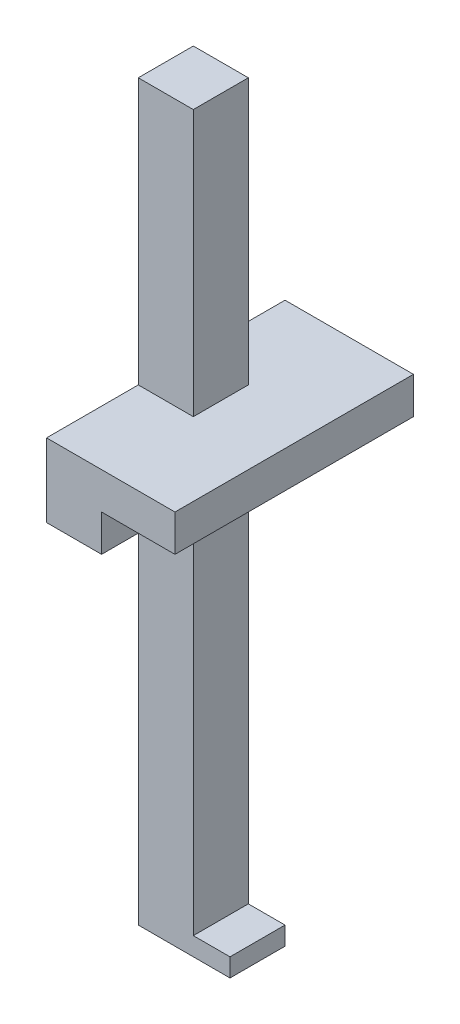
SolidWorks part; units mm, degrees
ref_plane "Front Plane" through (0, 0, 0) normal (0, 0, 1) x (1, 0, 0)
ref_plane "Top Plane" through (0, 0, 0) normal (0, 1, 0) x (1, 0, 0)
ref_plane "Right Plane" through (0, 0, 0) normal (1, 0, 0) x (0, 0, -1)
sketch "Sketch1" plane through (0, 0, 0) normal (0, 0, 1) x (1, 0, 0)
  line L0 (0, 0) -> (0, 40)
  line L1 (0, 40) -> (3, 40)
  line L2 (3, 40) -> (3, 1)
  line L3 (3, 1) -> (5, 1)
  line L4 (5, 1) -> (5, 0)
  line L5 (5, 0) -> (0, 0)
  dimension "D1" = 1
  dimension "D2" = 5
  dimension "D3" = 40
  dimension "D4" = 3
extrude "Boss-Extrude1" add sketch "Sketch1" along normal blind 3
sketch "Sketch2" plane through (0, 0, 3) normal (0, 0, 1) x (1, 0, 0)
  line L0 (0, 40) -> (0, 0) construction
  line L1 (0, 25.5) -> (3, 25.5)
  line L2 (0, 25.5) -> (0, 21.5)
  line L3 (0, 21.5) -> (3, 21.5)
  line L4 (3, 25.5) -> (3, 21.5)
  line L5 (3, 1) -> (3, 40) construction
  line L6 (0, 0) -> (5, 0) construction
  dimension "D1" = 4
  dimension "D2" = 21.5
extrude "Boss-Extrude2" add sketch "Sketch2" along normal blind 5
ref_plane "Plane1" through (0, 0, 1.5) normal (0, 0, 1) x (1, 0, 0)
mirror "Mirror1" about plane through (0, 0, 1.5) normal (0, 0, 1) of "Boss-Extrude2"
sketch "Sketch5" plane through (3, 0, 0) normal (1, 0, 0) x (0, 0, -1)
  line L0 (5, 21.5) -> (5, 25.5) construction
  line L1 (-8, 25.5) -> (5, 25.5)
  line L2 (-8, 25.5) -> (-8, 23.5)
  line L3 (-8, 23.5) -> (5, 23.5)
  line L4 (5, 25.5) -> (5, 23.5)
  dimension "D1" = 2
extrude "Boss-Extrude4" add sketch "Sketch5" along normal blind 4
